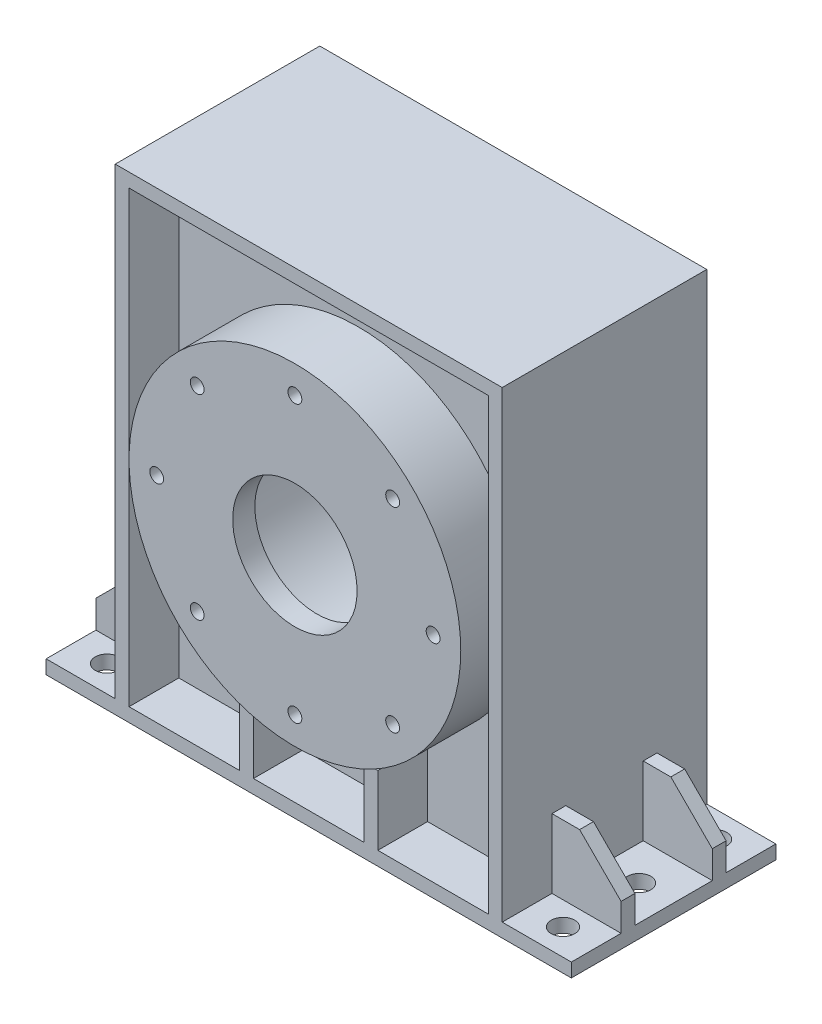
SolidWorks part; units mm, degrees
ref_plane "前视基准面" through (0, 0, 0) normal (0, 0, 1) x (1, 0, 0)
ref_plane "上视基准面" through (0, 0, 0) normal (0, 1, 0) x (1, 0, 0)
ref_plane "右视基准面" through (0, 0, 0) normal (1, 0, 0) x (0, 0, -1)
sketch "草图1" plane through (0, 0, 0) normal (0, 1, 0) x (1, 0, 0)
  line L1 (0, 0) -> (380, 0)
  line L2 (0, 0) -> (0, 148)
  line L3 (0, 148) -> (380, 148)
  line L4 (380, 0) -> (380, 148)
  dimension "D1" = 380
  dimension "D2" = 148
extrude "凸台-拉伸1" add sketch "草图1" along normal blind 10
sketch "草图2" plane through (0, 10, 0) normal (0, 1, 0) x (1, 0, 0)
  line L0 (380, 148) -> (0, 148) construction
  line L1 (50, 148) -> (60, 148)
  line L2 (50, 148) -> (50, 0)
  line L3 (50, 0) -> (60, 0)
  line L4 (60, 148) -> (60, 112)
  line L5 (0, 0) -> (380, 0) construction
  line L6 (190, -852) -> (190, 49148) construction
  line L7 (320, 148) -> (330, 148)
  line L8 (60, 112) -> (320, 112)
  line L9 (320, 0) -> (330, 0)
  line L10 (330, 148) -> (330, 0)
  line L11 (-1000, 74) -> (49000, 74) construction
  line L12 (0, 148) -> (0, 0) construction
  line L13 (320, 112) -> (320, 148)
  line L14 (60, 102) -> (320, 102)
  line L15 (320, 102) -> (320, 46)
  line L16 (320, 46) -> (60, 46)
  line L17 (60, 46) -> (60, 102)
  line L18 (60, 0) -> (60, 36)
  line L19 (60, 36) -> (320, 36)
  line L20 (320, 36) -> (320, 0)
  point P15 (190, 148)
  point P20 (0, 74)
  dimension "D1" = 10
  dimension "D2" = 10
  dimension "D3" = 280
  dimension "D4" = 10
  dimension "D5" = 10
  dimension "D6" = 56
extrude "凸台-拉伸2" add sketch "草图2" along normal blind 325
sketch "草图3" plane through (0, 335, 0) normal (0, 1, 0) x (1, 0, 0)
  line L1 (50, 148) -> (330, 148)
  line L2 (50, 148) -> (50, 0)
  line L3 (50, 0) -> (330, 0)
  line L4 (330, 148) -> (330, 0)
extrude "凸台-拉伸3" add sketch "草图3" along normal blind 10
sketch "草图4" plane through (0, 0, -36) normal (0, 0, 1) x (1, 0, 0)
  line L0 (190, -665) -> (190, 49335) construction
  line L1 (60, 335) -> (320, 335) construction
  line L2 (-767.6959, 175) -> (49232.3041, 175) construction
  line L3 (0, 0) -> (380, 0) construction
  circle A0 centre (190, 175) radius 120
  point P5 (190, 335)
  dimension "D2" = 240
  dimension "D1" = 175
extrude "切除-拉伸1" cut sketch "草图4" against normal through all
sketch "草图5" plane through (0, 0, 0) normal (0, 0, 1) x (1, 0, 0)
  circle A0 centre (190, 175) radius 120
  circle A1 centre (190, 175) radius 80
  circle A2 centre (190, 175) radius 120 construction
  dimension "D1" = 160
extrude "凸台-拉伸4" add sketch "草图5" against normal blind 148
sketch "草图6" plane through (0, 10, 0) normal (0, 1, 0) x (1, 0, 0)
  line L0 (190, -1000) -> (190, 49000) construction
  line L1 (60, 0) -> (320, 0) construction
  line L2 (60, 36) -> (320, 36) construction
  line L3 (140, 36) -> (150, 36)
  line L4 (140, 36) -> (140, 0)
  line L5 (140, 0) -> (150, 0)
  line L6 (150, 36) -> (150, 0)
  line L7 (320, 112) -> (60, 112) construction
  line L8 (230, 36) -> (240, 36)
  line L9 (230, 36) -> (230, 0)
  line L10 (230, 0) -> (240, 0)
  line L11 (240, 36) -> (240, 0)
  line L12 (240, 112) -> (230, 112)
  line L13 (240, 112) -> (240, 148)
  line L14 (240, 148) -> (230, 148)
  line L15 (230, 112) -> (230, 148)
  line L16 (320, 148) -> (60, 148) construction
  line L18 (150, 112) -> (140, 112)
  line L19 (150, 112) -> (150, 148)
  line L20 (150, 148) -> (140, 148)
  line L21 (140, 112) -> (140, 148)
  point P5 (190, 0)
  dimension "D1" = 10
  dimension "D2" = 10
  dimension "D3" = 80
extrude "凸台-拉伸5" add sketch "草图6" along normal blind 50
sketch "草图7" plane through (0, 10, 0) normal (0, 1, 0) x (1, 0, 0)
  line L0 (330, 0) -> (330, 148) construction
  line L1 (330, 36) -> (380, 36)
  line L2 (330, 36) -> (330, 46)
  line L3 (330, 46) -> (380, 46)
  line L4 (380, 36) -> (380, 46)
  line L5 (380, 0) -> (380, 148) construction
  line L6 (330, 102) -> (380, 102)
  line L7 (330, 102) -> (330, 112)
  line L8 (330, 112) -> (380, 112)
  line L9 (380, 102) -> (380, 112)
  line L10 (-620, 74) -> (49380, 74) construction
  line L11 (50, 148) -> (50, 0) construction
  line L12 (50, 112) -> (0, 112)
  line L13 (50, 112) -> (50, 102)
  line L14 (50, 102) -> (0, 102)
  line L15 (0, 112) -> (0, 102)
  line L16 (0, 148) -> (0, 0) construction
  line L18 (50, 46) -> (0, 46)
  line L19 (50, 46) -> (50, 36)
  line L20 (50, 36) -> (0, 36)
  line L21 (0, 46) -> (0, 36)
  point P15 (380, 74)
  dimension "D1" = 10
  dimension "D2" = 10
  dimension "D3" = 56
  dimension "D4" = 10
  dimension "D5" = 10
  dimension "D6" = 56
extrude "凸台-拉伸6" add sketch "草图7" along normal blind 50
sketch "草图8" plane through (0, 0, -112) normal (0, 0, -1) x (-1, 0, 0)
  line L0 (-380, 60) -> (-350, 60)
  line L1 (-380, 60) -> (-330, 60) construction
  line L2 (-350, 60) -> (-380, 30)
  line L3 (-380, 60) -> (-380, 10) construction
  line L4 (-380, 30) -> (-380, 60)
  line L5 (0, 60) -> (-30, 60)
  line L6 (-50, 60) -> (0, 60) construction
  line L7 (-30, 60) -> (0, 30)
  line L8 (0, 60) -> (0, 10) construction
  line L9 (0, 30) -> (0, 60)
  dimension "D1" = 30
  dimension "D2" = 30
  dimension "D3" = 30
  dimension "D4" = 30
extrude "切除-拉伸2" cut sketch "草图8" against normal through all
sketch "草图9" plane through (0, 0, 0) normal (0, 0, 1) x (1, 0, 0)
  circle A0 centre (190, 175) radius 65
  circle A1 centre (190, 175) radius 80
  circle A3 centre (190, 175) radius 80 construction
  dimension "D1" = 130
extrude "凸台-拉伸7" add sketch "草图9" against normal blind 14 separate body
sketch "草图10" plane through (0, 0, 0) normal (0, 0, 1) x (1, 0, 0)
  circle A0 centre (190, 175) radius 65
  circle A1 centre (190, 175) radius 65 construction
  circle A2 centre (190, 175) radius 45
  dimension "D1" = 90
extrude "凸台-拉伸8" add sketch "草图10" against normal blind 6
sketch "草图11" plane through (0, 0, 0) normal (0, 0, 1) x (1, 0, 0)
  circle A0 centre (190, 175) radius 120
  circle A2 centre (190, 175) radius 120 construction
  circle A3 centre (190, 175) radius 45
  circle A4 centre (190, 175) radius 45 construction
extrude "凸台-拉伸9" add sketch "草图11" along normal blind 10
sketch "草图12" plane through (0, 0, -148) normal (0, 0, -1) x (-1, 0, 0)
  circle A0 centre (-190, 175) radius 65
  circle A1 centre (-190, 175) radius 80
  circle A2 centre (-190, 175) radius 80 construction
  dimension "D1" = 130
extrude "凸台-拉伸10" add sketch "草图12" against normal blind 14
sketch "草图13" plane through (0, 0, -148) normal (0, 0, -1) x (-1, 0, 0)
  circle A1 centre (-190, 175) radius 65
  circle A2 centre (-190, 175) radius 65 construction
extrude "凸台-拉伸11" add sketch "草图13" against normal blind 5
sketch "草图14" plane through (0, 0, -148) normal (0, 0, -1) x (-1, 0, 0)
  circle A0 centre (-190, 175) radius 120
  circle A3 centre (-190, 175) radius 120 construction
extrude "凸台-拉伸12" add sketch "草图14" along normal blind 10
sketch "草图15" plane through (0, 0, 0) normal (0, -1, 0) x (1, 0, 0)
  line L0 (-1000, -74) -> (49000, -74) construction
  line L1 (0, -148) -> (0, 0) construction
  line L2 (190, -1148) -> (190, 48852) construction
  line L4 (-766.9636, -129) -> (49233.0364, -129) construction
  line L5 (-724.3332, -19) -> (49275.6668, -19) construction
  line L6 (100, -1049.4982) -> (100, 48950.5018) construction
  line L7 (280, -1060.4087) -> (280, 48939.5913) construction
  line L8 (380, -148) -> (0, -148) construction
  line L9 (25, -1104.8926) -> (25, 48895.1074) construction
  line L10 (355, -1085.765) -> (355, 48914.235) construction
  circle A0 centre (25, -129) radius 8.5
  circle A1 centre (25, -74) radius 8.5
  circle A2 centre (25, -19) radius 8.5
  circle A3 centre (190, -129) radius 8.5
  circle A4 centre (100, -129) radius 8.5
  circle A5 centre (280, -129) radius 8.5
  circle A6 centre (355, -74) radius 8.5
  circle A7 centre (355, -129) radius 8.5
  circle A8 centre (355, -19) radius 8.5
  point P5 (0, -74)
  point P21 (190, -148)
  dimension "D7" = 17
  dimension "D1" = 55
  dimension "D2" = 55
  dimension "D3" = 90
  dimension "D4" = 90
  dimension "D5" = 165
  dimension "D6" = 165
extrude "切除-拉伸3" cut sketch "草图15" against normal blind 10
sketch "草图16" plane through (0, 0, 10) normal (0, 0, 1) x (1, 0, 0)
  line L0 (190, -825) -> (190, 49175) construction
  line L1 (-810, 175) -> (49190, 175) construction
  circle A0 centre (190, 275) radius 5
  dimension "D2" = 10
  dimension "D1" = 100
extrude "切除-拉伸4" cut sketch "草图16" against normal blind 25
sketch "草图17" plane through (0, 0, -158) normal (0, 0, -1) x (-1, 0, 0)
  line L0 (-190, -825) -> (-190, 49175) construction
  line L1 (-1190, 175) -> (48810, 175) construction
  circle A0 centre (-190, 275) radius 5
  dimension "D1" = 10
  dimension "D2" = 100
extrude "切除-拉伸5" cut sketch "草图17" against normal blind 25
pattern_circular "阵列(圆周)1" count 8 over 360 about axis through (190, 175, 0) along (0, 0, 1) of "切除-拉伸4", "切除-拉伸5"
